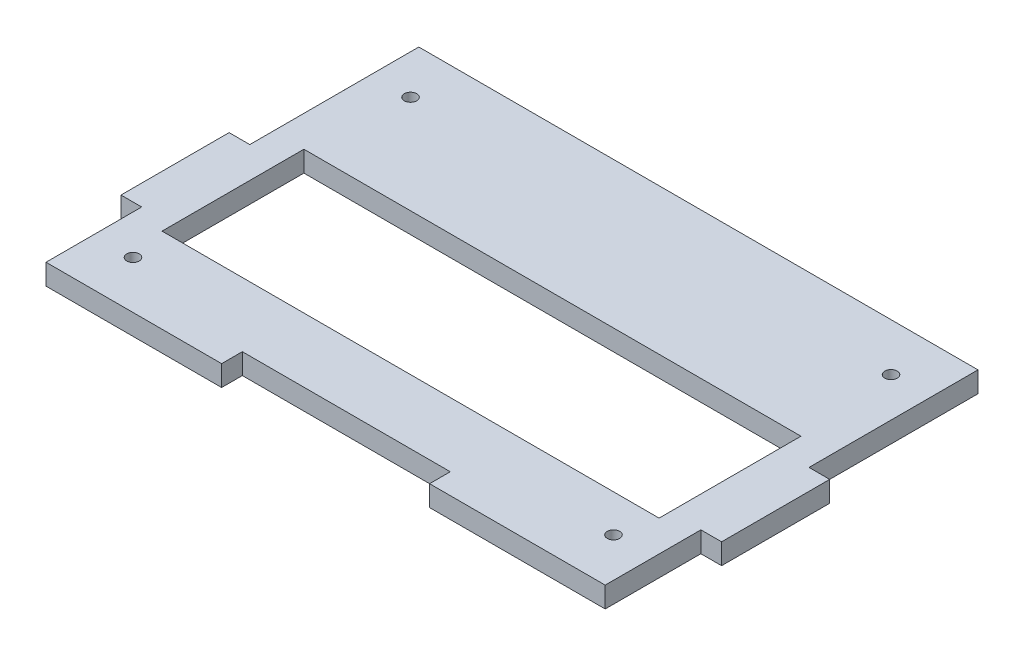
SolidWorks part; units mm, degrees
ref_plane "Front Plane" through (0, 0, 0) normal (0, 0, 1) x (1, 0, 0)
ref_plane "Top Plane" through (0, 0, 0) normal (0, 1, 0) x (1, 0, 0)
ref_plane "Right Plane" through (0, 0, 0) normal (1, 0, 0) x (0, 0, -1)
sketch "Sketch1" plane through (0, 0, 0) normal (0, 1, 0) x (1, 0, 0)
  line L1 (-72.5, -45) -> (72.5, -45)
  line L2 (-72.5, -45) -> (-72.5, 45)
  line L3 (-72.5, 45) -> (72.5, 45)
  line L4 (72.5, -45) -> (72.5, 45)
  line L5 (-72.5, -45) -> (72.5, 45) construction
  line L6 (-72.5, 45) -> (72.5, -45) construction
  point P0 (0, 0)
  dimension "D1" = 145
  dimension "D2" = 90
extrude "Boss-Extrude1" add sketch "Sketch1" along normal blind 5
sketch "Sketch3" plane through (0, 5, 0) normal (0, 1, 0) x (1, 0, 0)
  line L0 (0, -55) -> (0, 55) construction
  line L1 (-60, -24.49) -> (60, -24.49)
  line L2 (-60, -24.49) -> (-60, 9.76)
  line L3 (-60, 9.76) -> (60, 9.76)
  line L4 (60, -24.49) -> (60, 9.76)
  line L5 (-60, -24.49) -> (60, 9.76) construction
  line L6 (-60, 9.76) -> (60, -24.49) construction
  line L7 (-72.5, -45) -> (72.5, -45) construction
  point P0 (0, -7.365)
  dimension "D1" = 120
  dimension "D2" = 34.25
  dimension "D3" = 20.51
extrude "Cut-Extrude1" cut sketch "Sketch3" against normal blind 5
sketch "Sketch4" plane through (0, 5, 0) normal (0, 1, 0) x (1, 0, 0)
  line L0 (0, -2.75) -> (0, 2.75) construction
  line L1 (-72.5, 45) -> (-67.5, 45)
  line L2 (-72.5, 45) -> (-72.5, 4.2)
  line L3 (-72.5, 4.2) -> (-67.5, 4.2)
  line L4 (-67.5, 45) -> (-67.5, 4.2)
  line L5 (-72.5, -45) -> (-67.5, -45)
  line L6 (-72.5, -45) -> (-72.5, -21.9)
  line L7 (-72.5, -21.9) -> (-67.5, -21.9)
  line L8 (-67.5, -45) -> (-67.5, -21.9)
  line L9 (72.5, -21.9) -> (67.5, -21.9)
  line L10 (67.5, -45) -> (67.5, -21.9)
  line L11 (72.5, -45) -> (67.5, -45)
  line L12 (72.5, -45) -> (72.5, -21.9)
  line L13 (72.5, 4.2) -> (67.5, 4.2)
  line L14 (67.5, 45) -> (67.5, 4.2)
  line L15 (72.5, 45) -> (67.5, 45)
  line L16 (72.5, 45) -> (72.5, 4.2)
  dimension "D1" = 5
  dimension "D2" = 5
  dimension "D3" = 23.1
  dimension "D4" = 40.8
extrude "Cut-Extrude2" cut sketch "Sketch4" against normal blind 5
sketch "Sketch7" plane through (0, 5, 0) normal (0, 1, 0) x (1, 0, 0)
  line L0 (0, -2.75) -> (0, 2.75) construction
  line L1 (-25.1, -40) -> (25.1, -40)
  line L2 (-25.1, -40) -> (-25.1, -45)
  line L3 (-25.1, -45) -> (25.1, -45)
  line L4 (25.1, -40) -> (25.1, -45)
  line L5 (-25.1, -40) -> (25.1, -45) construction
  line L6 (-25.1, -45) -> (25.1, -40) construction
  line L7 (-67.5, -45) -> (67.5, -45) construction
  point P0 (0, -42.5)
  dimension "D1" = 5
  dimension "D2" = 50.2
extrude "Cut-Extrude3" cut sketch "Sketch7" against normal blind 5
sketch "Sketch9" plane through (0, 5, 0) normal (0, 1, 0) x (1, 0, 0)
  line L1 (-58, -33.5) -> (58, -33.5) construction
  line L2 (-58, -33.5) -> (-58, 33.5) construction
  line L3 (-58, 33.5) -> (58, 33.5) construction
  line L4 (58, -33.5) -> (58, 33.5) construction
  line L5 (-58, -33.5) -> (58, 33.5) construction
  line L6 (-58, 33.5) -> (58, -33.5) construction
  circle A0 centre (-58, 33.5) radius 1.5
  circle A1 centre (58, 33.5) radius 1.5
  circle A2 centre (58, -33.5) radius 1.5
  circle A3 centre (-58, -33.5) radius 1.5
  point P0 (0, 0)
  dimension "D3" = 3
  dimension "D4" = 3
  dimension "D5" = 3
  dimension "D6" = 3
  dimension "D1" = 116
  dimension "D2" = 67
extrude "Cut-Extrude4" cut sketch "Sketch9" against normal blind 10
